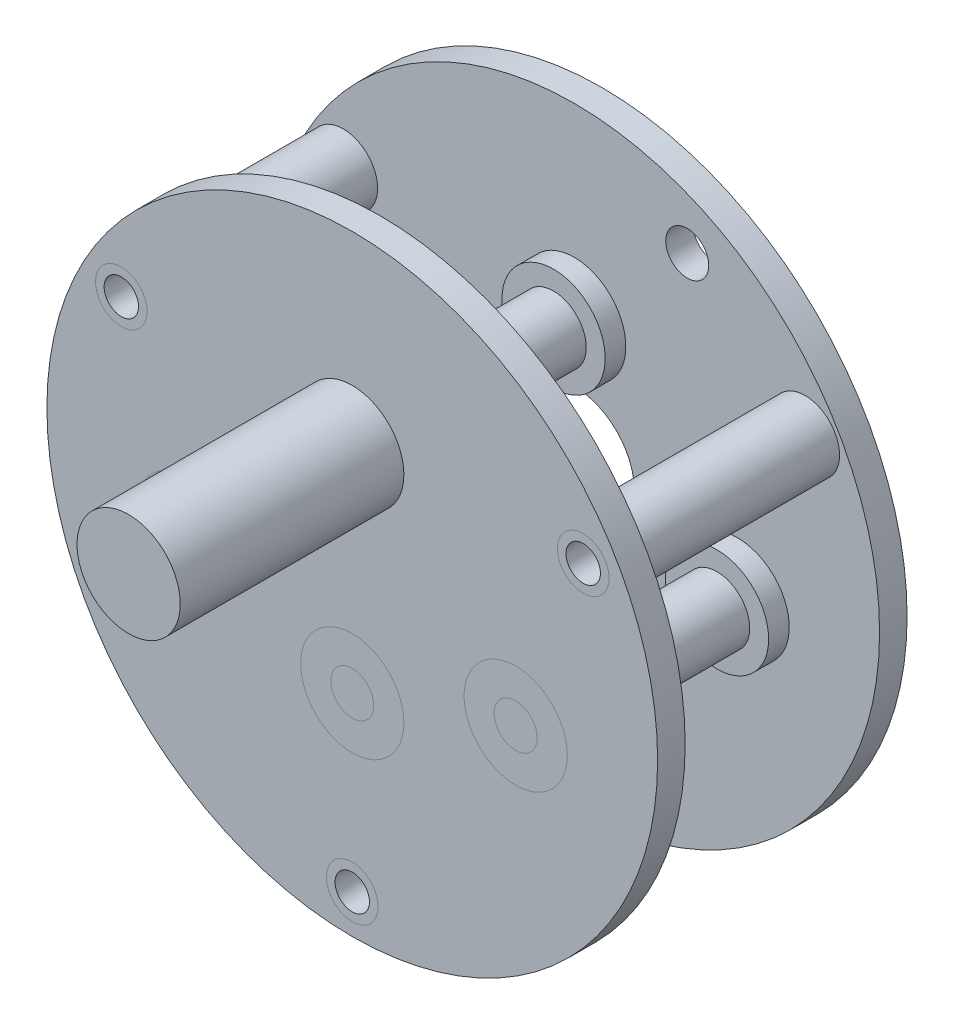
SolidWorks part; units mm, degrees
ref_plane "正面" through (0, 0, 0) normal (0, 0, 1) x (1, 0, 0)
ref_plane "平面" through (0, 0, 0) normal (0, 1, 0) x (1, 0, 0)
ref_plane "右側面" through (0, 0, 0) normal (1, 0, 0) x (0, 0, -1)
sketch "ｽｹｯﾁ1" plane through (0, 0, 0) normal (0, 0, 1) x (1, 0, 0)
  circle A0 centre (0, 0) radius 17.75
  dimension "D1" = 35.5
extrude "ﾎﾞｽ - 押し出し1" add sketch "ｽｹｯﾁ1" along normal blind 1.6
sketch "ｽｹｯﾁ2" plane through (0, 0, 0) normal (0, 0, -1) x (-1, 0, 0)
  circle A0 centre (0, -15.5) radius 2
  circle A2 centre (0, 0) radius 17.75 construction
  circle A3 centre (-13.4234, 7.75) radius 2
  circle A5 centre (13.4234, 7.75) radius 2
  point P14 (0, 0)
  dimension "D1" = 4
  dimension "D2" = 15.5
  dimension "D3" = 3
extrude "ﾎﾞｽ - 押し出し2" add sketch "ｽｹｯﾁ2" along normal blind 11.3
sketch "ｽｹｯﾁ3" plane through (0, 0, -11.3) normal (0, 0, -1) x (-1, 0, 0)
  circle A0 centre (0, 0) radius 17.75
  circle A1 centre (0, 0) radius 17.75 construction
extrude "ﾎﾞｽ - 押し出し3" add sketch "ｽｹｯﾁ3" along normal blind 1.6
sketch "ｽｹｯﾁ5" plane through (0, 0, -12.9) normal (0, 0, -1) x (-1, 0, 0)
  circle A0 centre (0, -15.5) radius 2 construction
  circle A1 centre (13.4234, 7.75) radius 2 construction
  circle A2 centre (-13.4234, 7.75) radius 2 construction
  circle A3 centre (0, -15.5) radius 2 construction
  circle A4 centre (13.4234, 7.75) radius 2 construction
  circle A5 centre (-13.4234, 7.75) radius 2 construction
  circle A6 centre (0, 0) radius 3.5
  circle A7 centre (-13.4234, 7.75) radius 1
  circle A8 centre (13.4234, 7.75) radius 1
  circle A9 centre (0, -15.5) radius 1
  dimension "D1" = 7
  dimension "D2" = 1
extrude "ｶｯﾄ - 押し出し2" cut sketch "ｽｹｯﾁ5" against normal up to next
sketch "ｽｹｯﾁ6" plane through (0, 0, 1.6) normal (0, 0, 1) x (1, 0, 0)
  circle A0 centre (0, 7) radius 6
  circle A1 centre (0, 0) radius 17.75 construction
  dimension "D1" = 7
  dimension "D2" = 12
extrude "ﾎﾞｽ - 押し出し4" add sketch "ｽｹｯﾁ6" along normal blind 10
sketch "ｽｹｯﾁ7" plane through (0, 0, 11.6) normal (0, 0, 1) x (1, 0, 0)
  circle A0 centre (0, 7) radius 3
  dimension "D1" = 6
extrude "ﾎﾞｽ - 押し出し5" add sketch "ｽｹｯﾁ7" along normal blind 15
chamfer "面取り1" distance 0.5 angle 45 1 edges at (3, 7, 26.6)
sketch "ｽｹｯﾁ8" plane through (0, 0, 26.6) normal (0, 0, 1) x (1, 0, 0)
  line L0 (1.6583, 9.5) -> (-1.6583, 9.5)
  circle A0 centre (0, 7) radius 3 construction
  arc A1 (1.6583, 9.5) -> (-1.6583, 9.5) centre (0, 7) ccw
  dimension "D1" = 2.5
extrude "ｶｯﾄ - 押し出し3" cut sketch "ｽｹｯﾁ8" against normal blind 12
sketch "ｽｹｯﾁ9" plane through (0, 0, 1.6) normal (0, 0, 1) x (1, 0, 0)
  circle A4 centre (0, -15.5) radius 1.5
  circle A5 centre (-13.4234, 7.75) radius 1.5
  circle A6 centre (13.4234, 7.75) radius 1.5
  point P9 (0, 0)
  dimension "D1" = 3
  dimension "D2" = 3
split line "分割ﾗｲﾝ1"
sketch "ｽｹｯﾁ10" plane through (0, 0, 1.6) normal (0, 0, 1) x (1, 0, 0)
  line L0 (-9.5, -2.3775) -> (0, -5.5) construction
  line L1 (0, -5.5) -> (9.5, -2.3775) construction
  circle A0 centre (0, -5.5) radius 3
  circle A1 centre (9.5, -2.3775) radius 3
  circle A2 centre (-9.5, -2.3775) radius 3
  circle A3 centre (0, 0) radius 17.75 construction
  dimension "D2" = 5.5
  dimension "D3" = 19
  dimension "D4" = 6
  dimension "D1" = 10
extrude "ﾎﾞｽ - 押し出し6" add sketch "ｽｹｯﾁ10" against normal blind 2.8
ref_plane "平面1" through (0, 0, -5.65) normal (0, 0, 1) x (1, 0, 0)
mirror "ﾐﾗｰ1" about plane through (0, 0, -5.65) normal (0, 0, 1) of "ﾎﾞｽ - 押し出し6"
sketch "ｽｹｯﾁ11" plane through (0, 0, 1.6) normal (0, 0, 1) x (1, 0, 0)
  circle A0 centre (0, -5.5) radius 3 construction
  circle A1 centre (-9.5, -2.3775) radius 3 construction
  circle A2 centre (9.5, -2.3775) radius 3 construction
  circle A3 centre (0, -5.5) radius 3
  circle A4 centre (-9.5, -2.3775) radius 3
  circle A5 centre (9.5, -2.3775) radius 3
split line "分割ﾗｲﾝ2"
sketch "ｽｹｯﾁ12" plane through (0, 0, 1.6) normal (0, 0, 1) x (1, 0, 0)
  circle A0 centre (-9.5, -2.3775) radius 1.25
  circle A1 centre (0, -5.5) radius 1.25
  circle A2 centre (9.5, -2.3775) radius 1.25
  circle A3 centre (-9.5, -2.3775) radius 3 construction
  circle A9 centre (0, -5.5) radius 3 construction
  circle A10 centre (9.5, -2.3775) radius 3 construction
  dimension "D1" = 2.5
split line "分割ﾗｲﾝ3"
sketch "ｽｹｯﾁ13" plane through (0, 0, -1.2) normal (0, 0, -1) x (-1, 0, 0)
  circle A1 centre (-9.5, -2.3775) radius 1.9
  circle A2 centre (0, -5.5) radius 1.9
  circle A3 centre (9.5, -2.3775) radius 1.9
  dimension "D1" = 3.8
extrude "ﾎﾞｽ - 押し出し7" add sketch "ｽｹｯﾁ13" along normal up to next
sketch "ｽｹｯﾁ14" plane through (0, 0, -12.9) normal (0, 0, -1) x (-1, 0, 0)
  circle A0 centre (0, 7) radius 6 construction
  circle A1 centre (0, 7) radius 1.25
  circle A2 centre (0, -5.5) radius 1.25 construction
  circle A6 centre (0, 7) radius 3
  circle A9 centre (0, -5.5) radius 3 construction
split line "分割ﾗｲﾝ4"
sketch "ｽｹｯﾁ15" plane through (0, 0, -12.9) normal (0, 0, -1) x (-1, 0, 0)
  line L0 (2.2361, -3.5) -> (-2.2361, -3.5)
  arc A0 (-1.7249, -3.0455) -> (1.7249, -3.0455) centre (0, -5.5) ccw construction
  arc A2 (1.7249, -3.0455) -> (-1.7249, -3.0455) centre (0, 0) ccw construction
  arc A3 (2.2361, -3.5) -> (1.7249, -3.0455) centre (0, -5.5) ccw
  arc A5 (-1.7249, -3.0455) -> (1.7249, -3.0455) centre (0, -5.5) ccw
  arc A6 (1.7249, -3.0455) -> (-1.7249, -3.0455) centre (0, -5.5) ccw
  arc A7 (-1.7249, -3.0455) -> (-2.2361, -3.5) centre (0, -5.5) ccw
  arc A8 (1.7249, -3.0455) -> (-1.7249, -3.0455) centre (0, -5.5) ccw
  dimension "D1" = 0
extrude "ｶｯﾄ - 押し出し4" cut sketch "ｽｹｯﾁ15" against normal up to next
sketch "ｽｹｯﾁ17" plane through (0, 0, -12.9) normal (0, 0, -1) x (-1, 0, 0)
  line L0 (6.5696, -13.4848) -> (-6.5696, 13.4848) construction
  line L1 (9.5, -2.3775) -> (-6.5696, 13.4848) construction
  circle A0 centre (-6.5696, 13.4848) radius 1.25
  circle A1 centre (6.5696, -13.4848) radius 1.25
  circle A2 centre (0, 7) radius 1.25 construction
  circle A3 centre (9.5, -2.3775) radius 1.25 construction
  point P6 (0, 0)
  point P7 (0, 7)
  dimension "D2" = 2.5
  dimension "D1" = 30
extrude "ｶｯﾄ - 押し出し5" cut sketch "ｽｹｯﾁ17" against normal up to next
chamfer "面取り2" distance 0.5 angle 45 1 edges at (6, 7, 11.6)
sketch "ｽｹｯﾁ19" plane through (0, 0, 0) normal (0, 0, -1) x (-1, 0, 0)
  circle A0 centre (0, 7) radius 3 construction
  circle A1 centre (0, 7) radius 3
extrude "ﾎﾞｽ - 押し出し8" add sketch "ｽｹｯﾁ19" along normal up to surface (1.2 mm away) up to face at (1.9, -5.5, -1.2)
sketch "ｽｹｯﾁ20" plane through (0, 0, -1.2) normal (0, 0, -1) x (-1, 0, 0)
  circle A0 centre (0, 7) radius 1.9
  circle A1 centre (0, -5.5) radius 1.9 construction
extrude "ﾎﾞｽ - 押し出し9" add sketch "ｽｹｯﾁ20" along normal up to next
sketch "ｽｹｯﾁ21" plane through (0, 0, -11.3) normal (0, 0, 1) x (1, 0, 0)
  circle A0 centre (0, 7) radius 3 construction
  circle A1 centre (0, 7) radius 3
extrude "ﾎﾞｽ - 押し出し10" add sketch "ｽｹｯﾁ21" along normal up to surface (1.2 mm away) up to face at (7.6, -2.3775, -10.1)
sketch "ｽｹｯﾁ22" plane through (0, 0, 11.6) normal (0, 0, 1) x (1, 0, 0)
  circle A0 centre (0, 7) radius 6
  circle A1 centre (0, 7) radius 3
  arc A2 (1.6583, 9.5) -> (-1.6583, 9.5) centre (0, 7) ccw construction
  circle A3 centre (0, 7) radius 6 construction
extrude "ｶｯﾄ - 押し出し6" cut sketch "ｽｹｯﾁ22" against normal up to surface (10 mm away) up to face at (-6.5, -2.3775, 1.6)
sketch "ｽｹｯﾁ24" plane through (0, 0, 26.6) normal (0, 0, 1) x (1, 0, 0)
  circle A0 centre (0, 7) radius 3
  arc A1 (1.6583, 9.5) -> (-1.6583, 9.5) centre (0, 7) ccw construction
extrude "ｶｯﾄ - 押し出し8" cut sketch "ｽｹｯﾁ24" against normal blind 12
